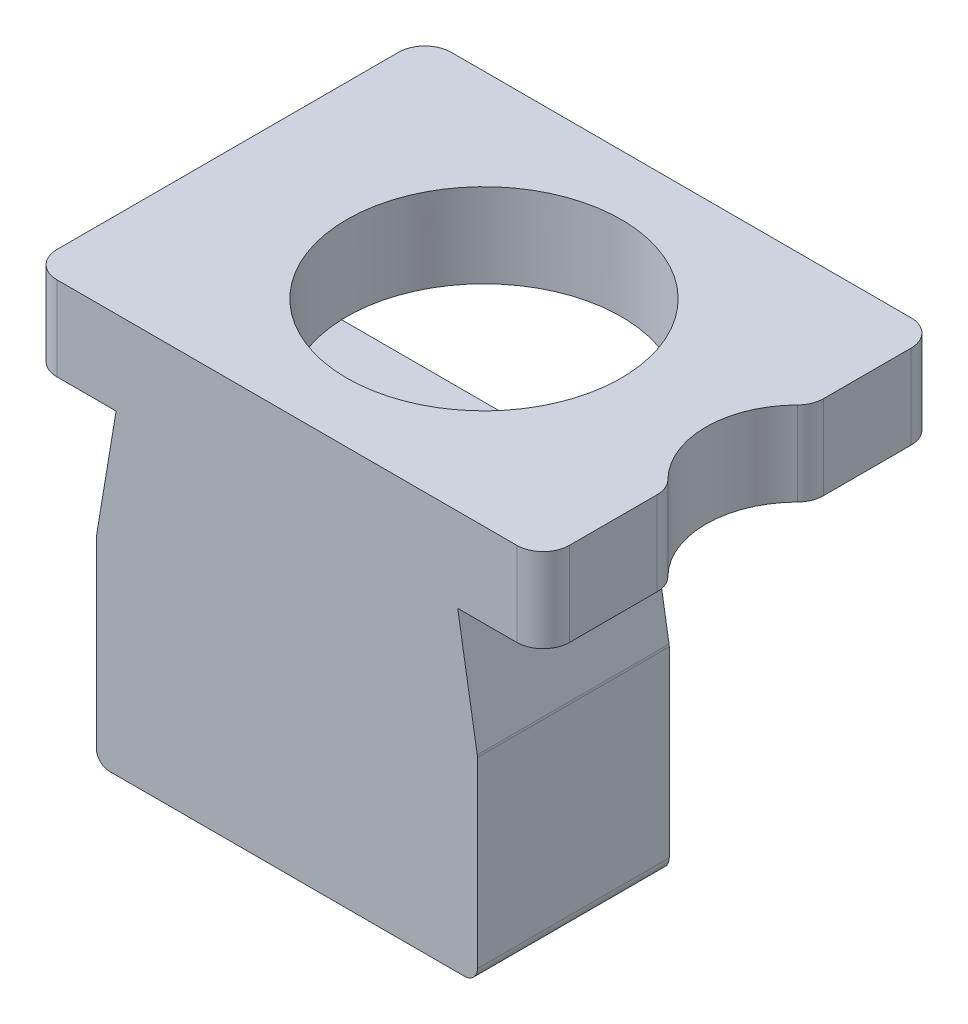
SolidWorks part; units mm, degrees
ref_plane "Front Plane" through (0, 0, 0) normal (0, 0, 1) x (1, 0, 0)
ref_plane "Top Plane" through (0, 0, 0) normal (0, 1, 0) x (1, 0, 0)
ref_plane "Right Plane" through (0, 0, 0) normal (1, 0, 0) x (0, 0, -1)
sketch "Sketch1" plane through (0, 0, 0) normal (0, 1, 0) x (1, 0, 0)
  line L1 (-19.5, -15) -> (19.5, -15)
  line L2 (-19.5, -15) -> (-19.5, 15)
  line L3 (-19.5, 15) -> (19.5, 15)
  line L4 (19.5, -15) -> (19.5, 15)
  line L5 (-19.5, -15) -> (19.5, 15) construction
  line L6 (-19.5, 15) -> (19.5, -15) construction
  circle A0 centre (0, 0) radius 10.45
  point P0 (0, 0)
  dimension "D3" = 20.9
  dimension "D1" = 30
  dimension "D2" = 39
extrude "Boss-Extrude1" add sketch "Sketch1" along normal blind 6.4
sketch "Sketch2" plane through (0, 0, 15) normal (0, 0, 1) x (1, 0, 0)
  line L0 (-13, 0) -> (-14.5, -9)
  line L1 (-19.5, 0) -> (19.5, 0) construction
  line L2 (-14.5, -9) -> (-14.5, -24)
  line L3 (-14.5, -24) -> (14.5, -24)
  line L4 (0, -24) -> (0, 0) construction
  line L5 (13, 0) -> (-13, 0)
  line L6 (14.5, -9) -> (14.5, -24)
  line L7 (13, 0) -> (14.5, -9)
  dimension "D1" = 24
  dimension "D2" = 29
  dimension "D3" = 26
  dimension "D4" = 15
extrude "Boss-Extrude2" add sketch "Sketch2" against normal blind 14.6
sketch "Sketch3" plane through (0, 6.4, 0) normal (0, 1, 0) x (1, 0, 0)
  line L1 (0, 0) -> (23.8929, 0) construction
  line L2 (19.5, -15) -> (19.5, 15) construction
  line L3 (19.5, 5.45) -> (19.5, -5.45)
  arc A1 (19.5, 5.45) -> (19.5, -5.45) centre (23.8929, 0) ccw
  point P3 (19.5, 5.45)
  point P4 (19.5, -5.45)
  dimension "D1" = 10.9
  dimension "D2" = 14
extrude "Cut-Extrude1" cut sketch "Sketch3" against normal up to surface (6.4 mm away) up to face at (0, 0, 2.075)
fillet "Fillet1" radius 2 6 edges at (19.5, 3.2, -5.45) (19.5, 3.2, 5.45) (-19.5, 3.2, -15) (-19.5, 3.2, 15) (19.5, 3.2, 15) (19.5, 3.2, -15)
fillet "Fillet2" radius 1 4 edges at (-14.5, -9, 7.7) (14.5, -9, 7.7) (-14.5, -24, 7.7) (14.5, -24, 7.7)
